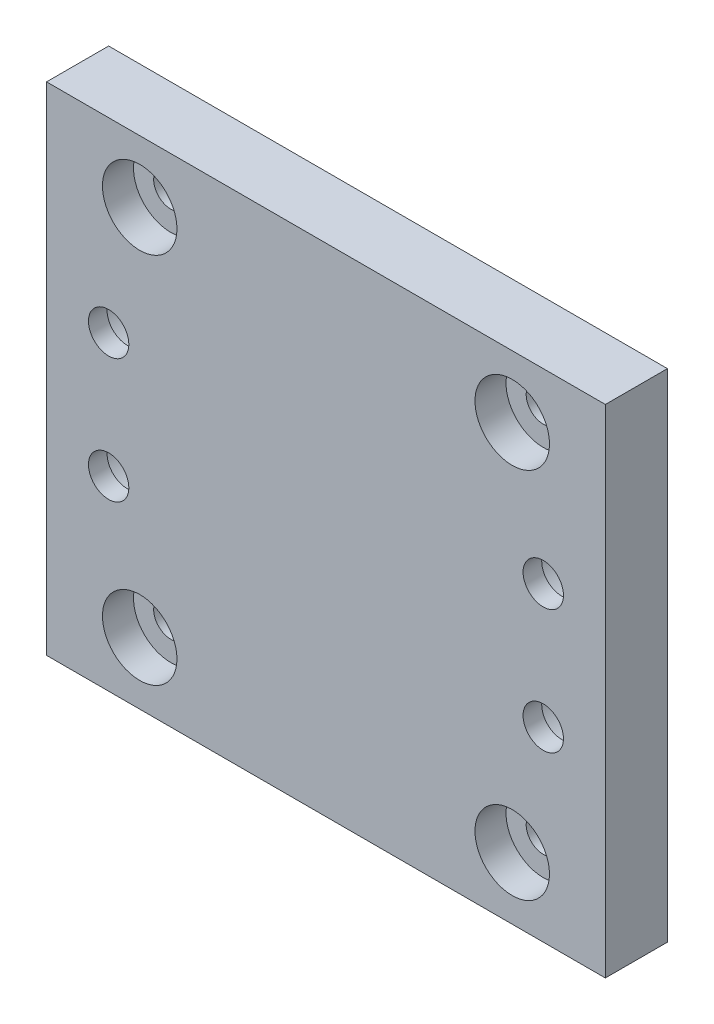
SolidWorks part; units mm, degrees
ref_plane "Plan de face" through (0, 0, 0) normal (0, 0, 1) x (1, 0, 0)
ref_plane "Plan de dessus" through (0, 0, 0) normal (0, 1, 0) x (1, 0, 0)
ref_plane "Plan de droite" through (0, 0, 0) normal (1, 0, 0) x (0, 0, -1)
sketch "Esquisse1" plane through (0, 0, 0) normal (0, 0, 1) x (1, 0, 0)
  line L0 (-32.4328, -23.2116) -> (27.5672, -23.2116) construction
  line L1 (-47.4328, 46.7884) -> (42.5672, 46.7884)
  line L2 (-47.4328, 46.7884) -> (-47.4328, -33.2116)
  line L3 (-47.4328, -33.2116) -> (42.5672, -33.2116)
  line L4 (42.5672, 46.7884) -> (42.5672, -33.2116)
  line L6 (-32.4328, 36.7884) -> (-32.4328, 46.7884) construction
  line L8 (27.5672, 36.7884) -> (27.5672, 46.7884) construction
  line L9 (-32.4328, -23.2116) -> (-32.4328, -33.2116) construction
  line L12 (27.5672, -23.2116) -> (27.5672, -33.2116) construction
  line L13 (-37.4328, 16.7884) -> (-37.4328, -3.2116) construction
  line L14 (-37.4328, -3.2116) -> (32.5672, -3.2116) construction
  circle A0 centre (-32.4328, 36.7884) radius 2.75
  circle A1 centre (27.5672, 36.7884) radius 2.75
  circle A2 centre (27.5672, -23.2116) radius 2.75
  circle A3 centre (-32.4328, -23.2116) radius 2.75
  circle A4 centre (-37.4328, 16.7884) radius 3.25
  circle A5 centre (-37.4328, -3.2116) radius 3.25
  circle A6 centre (32.5672, 16.7884) radius 3.25
  circle A7 centre (32.5672, -3.2116) radius 3.25
  point P13 (-2.4328, -23.2116)
  point P15 (0, 0)
  point P18 (0, 0)
  point P19 (0, 0)
  point P28 (-2.4328, -3.2116)
  point P29 (-37.4328, 6.7884)
  point P30 (-2.4328, -33.2116)
  point P31 (-47.4328, 6.7884)
  dimension "D3" = 5.5
  dimension "D5" = 6.5
  dimension "D1" = 90
  dimension "D2" = 80
  dimension "D4" = 10
  dimension "D6" = 70
  dimension "D7" = 20
  dimension "D8" = 60
extrude "Boss.-Extru.1" add sketch "Esquisse1" along normal blind 10
sketch "Esquisse2" plane through (0, 0, 10) normal (0, 0, 1) x (1, 0, 0)
  circle A0 centre (-32.4328, 36.7884) radius 6
  circle A1 centre (27.5672, 36.7884) radius 6
  circle A2 centre (27.5672, -23.2116) radius 6
  circle A3 centre (-32.4328, -23.2116) radius 6
  dimension "D1" = 12
extrude "Enlèv. mat.-Extru.1" cut sketch "Esquisse2" against normal blind 5
sketch "Esquisse4" plane through (0, 0, 0) normal (0, 0, -1) x (-1, 0, 0)
  circle A0 centre (-32.5672, 16.7884) radius 7
  circle A1 centre (37.4328, 16.7884) radius 7
  circle A2 centre (37.4328, -3.2116) radius 7
  circle A3 centre (-32.5672, -3.2116) radius 7
  dimension "D1" = 14
extrude "Enlèv. mat.-Extru.2" cut sketch "Esquisse4" against normal blind 7
